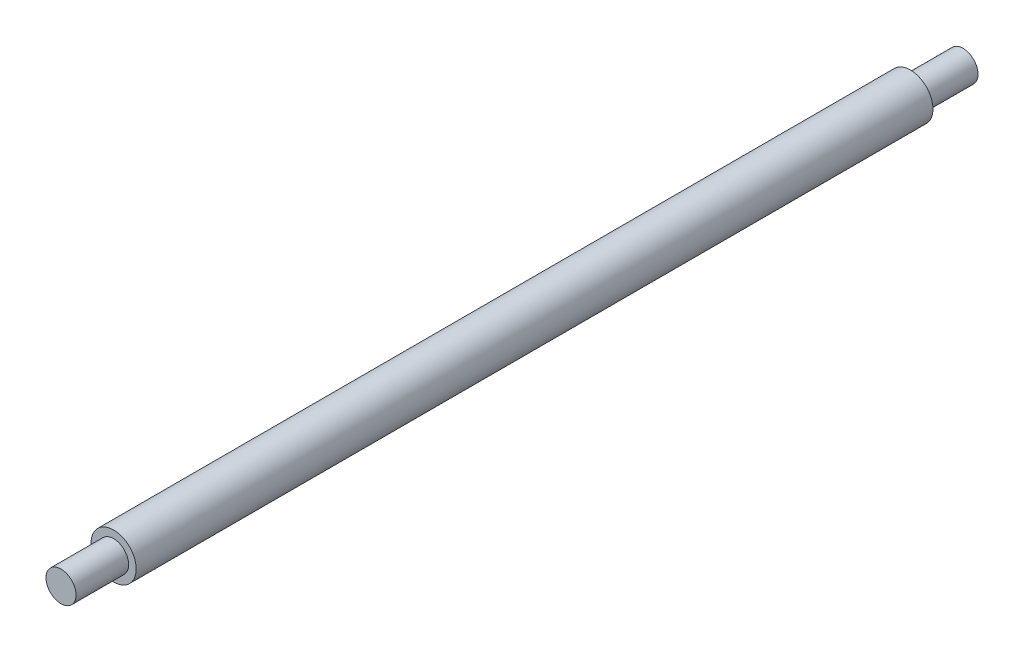
SolidWorks part; units mm, degrees
material "6061 Alloy"
ref_plane "Front" through (0, 0, 0) normal (0, 0, 1) x (1, 0, 0)
ref_plane "Top" through (0, 0, 0) normal (0, 1, 0) x (1, 0, 0)
ref_plane "Right" through (0, 0, 0) normal (1, 0, 0) x (0, 0, -1)
sketch "Sketch1" plane through (0, 0, 0) normal (0, 0, 1) x (1, 0, 0)
  circle A0 centre (0, 0) radius 9.525
  dimension "D1" = 19.05
extrude "Boss-Extrude1" add sketch "Sketch1" along normal blind 336.55
sketch "Sketch2" plane through (0, 0, 336.55) normal (0, 0, 1) x (1, 0, 0)
  circle A0 centre (0, 0) radius 6.35
  dimension "D1" = 12.7
extrude "Boss-Extrude2" add sketch "Sketch2" along normal blind 22.225
sketch "Sketch3" plane through (0, 0, 0) normal (0, 0, -1) x (-1, 0, 0)
  circle A0 centre (0, 0) radius 6.35
  dimension "D1" = 12.7
extrude "Boss-Extrude3" add sketch "Sketch3" along normal blind 22.225
